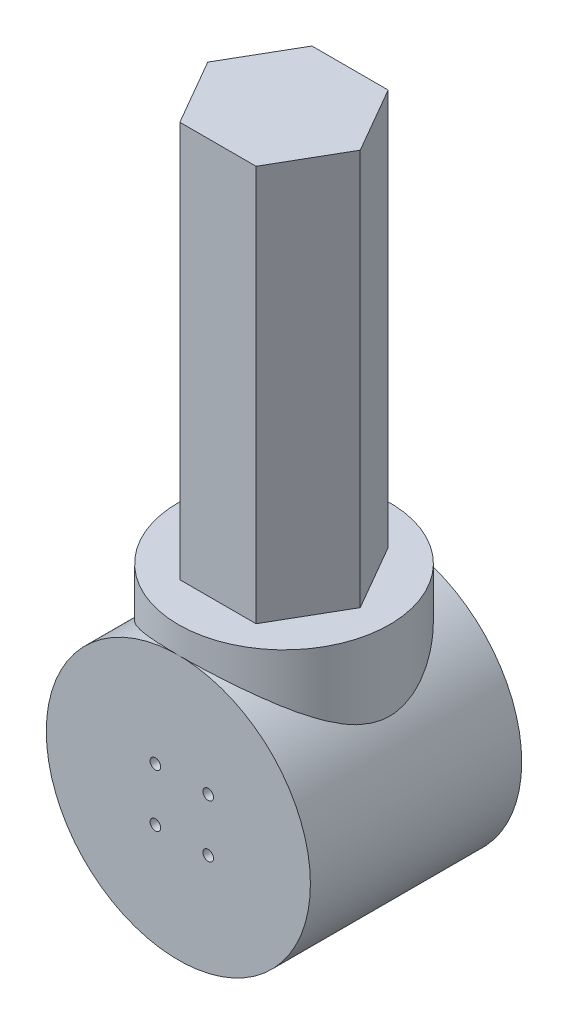
SolidWorks part; units mm, degrees
ref_plane "Front Plane" through (0, 0, 0) normal (0, 0, 1) x (1, 0, 0)
ref_plane "Top Plane" through (0, 0, 0) normal (0, 1, 0) x (1, 0, 0)
ref_plane "Right Plane" through (0, 0, 0) normal (1, 0, 0) x (0, 0, -1)
sketch "Sketch1" plane through (0, 0, 0) normal (0, 0, 1) x (1, 0, 0)
  circle A1 centre (0, 0) radius 25
  dimension "D2" = 50
extrude "Boss-Extrude1" add sketch "Sketch1" along normal blind 40
ref_plane "Plane1" through (0, 5, 0) normal (0, 1, 0) x (1, 0, 0)
sketch "Sketch2" plane through (0, 5, 0) normal (0, 1, 0) x (1, 0, 0)
  line L1 (-25, -19.6012) -> (-19.996, -19.6012)
  line L2 (-25, 0) -> (-25, -40) construction
  line L3 (-20, -20) -> (-22.5, -20)
  circle A0 centre (0, -20) radius 20
  dimension "D3" = 40
extrude "Boss-Extrude2" add sketch "Sketch2" along normal blind 25 separate body contours A0
sketch "Sketch3" plane through (0, 30, 0) normal (0, 1, 0) x (1, 0, 0)
  line L0 (0, 0) -> (0, -20)
  line L1 (0, -20) -> (20, -20)
  line L3 (14.4338, -20) -> (7.2169, -7.5)
  line L4 (7.2169, -7.5) -> (-7.2169, -7.5)
  line L5 (-7.2169, -7.5) -> (-14.4338, -20)
  line L6 (-14.4338, -20) -> (-7.2169, -32.5)
  line L7 (-7.2169, -32.5) -> (7.2169, -32.5)
  line L8 (7.2169, -32.5) -> (14.4338, -20)
  circle A0 centre (0, -20) radius 20 construction
  circle A1 centre (0, -20) radius 12.5 construction
extrude "Boss-Extrude3" add sketch "Sketch3" along normal blind 25 contours L7 L8 L1 L0 L4 L5 L6 | L3 L4 L0 L1
sketch "Sketch4" plane through (0, 55, 0) normal (0, 1, 0) x (1, 0, 0)
  line L1 (7.2169, -32.5) -> (14.4338, -20)
  line L2 (14.4338, -20) -> (7.2169, -7.5)
  line L3 (7.2169, -7.5) -> (-7.2169, -7.5)
  line L4 (-7.2169, -7.5) -> (-14.4338, -20)
  line L5 (-14.4338, -20) -> (-7.2169, -32.5)
  line L6 (-7.2169, -32.5) -> (7.2169, -32.5)
  circle A0 centre (0, -20) radius 12.5 construction
extrude "Boss-Extrude4" add sketch "Sketch4" along normal blind 50
sketch "Sketch5" plane through (0, 0, 0) normal (0, 0, -1) x (-1, 0, 0)
  line L0 (0, 25) -> (24.3456, 25)
  line L1 (24.3456, 25) -> (24.3456, -9.0701)
  circle A0 centre (-5.6544, 5) radius 1
  circle A1 centre (4.3456, 5) radius 1
  circle A2 centre (4.3456, -5) radius 1
  circle A3 centre (-5.6544, -5) radius 1
  circle A5 centre (0, 0) radius 25 construction
  point P12 (0, 0)
  dimension "D1" = 2
  dimension "D2" = 10
  dimension "D3" = 10
  dimension "D4" = 10
  dimension "D5" = 10
  dimension "D6" = 20
  dimension "D7" = 20
extrude "Cut-Extrude1" cut sketch "Sketch5" against normal blind 50 contours A0 | A1 | A2 | A3
